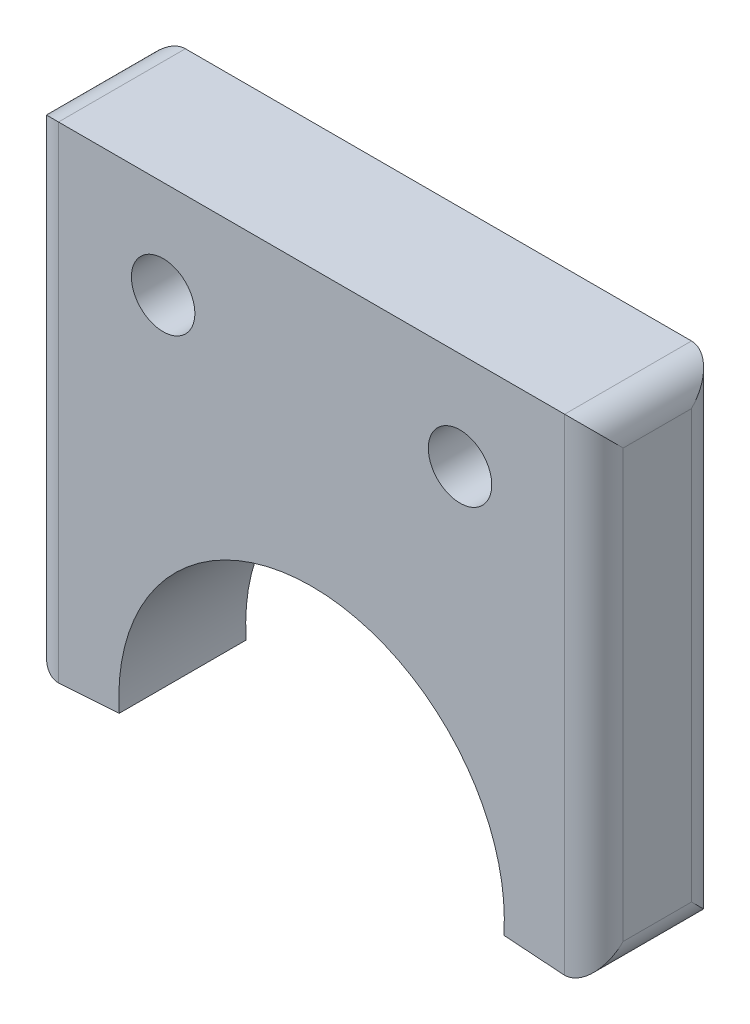
SolidWorks part; units mm, degrees
ref_plane "Front Plane" through (0, 0, 0) normal (0, 0, 1) x (1, 0, 0)
ref_plane "Top Plane" through (0, 0, 0) normal (0, 1, 0) x (1, 0, 0)
ref_plane "Right Plane" through (0, 0, 0) normal (1, 0, 0) x (0, 0, -1)
sketch "Sketch2" plane through (0, 0, 0) normal (0, 0, 1) x (1, 0, 0)
  line L0 (-19.7019, -1.3777) -> (-28.9294, -2.0229)
  line L1 (0, 0) -> (0, 53.2541) construction
  line L2 (19.7019, -1.3777) -> (28.9294, -2.0229)
  line L3 (-28.9294, -2.0229) -> (-28.9294, 47.9771)
  line L4 (28.9294, -2.0229) -> (28.9294, 47.9771)
  line L5 (-28.9294, 47.9771) -> (28.9294, 47.9771)
  arc A0 (19.7019, -1.3777) -> (-19.7019, -1.3777) centre (0, 0) ccw
  circle A2 centre (15.2099, 37.9771) radius 3.25
  circle A3 centre (-15.2099, 37.9771) radius 3.25
  dimension "D1" = 39.5
  dimension "D2" = 94
  dimension "D3" = 6.5
  dimension "D4" = 10
extrude "Boss-Extrude1" add sketch "Sketch2" along normal blind 13
fillet "Fillet1" radius 3 8 edges at (-28.9294, 47.9771, 6.5) (-28.9294, 22.9771, 13) (-28.9294, -2.0229, 6.5) (-28.9294, 22.9771, 0) (28.9294, -2.0229, 6.5) (28.9294, 22.9771, 13) (28.9294, 47.9771, 6.5) (28.9294, 22.9771, 0)
